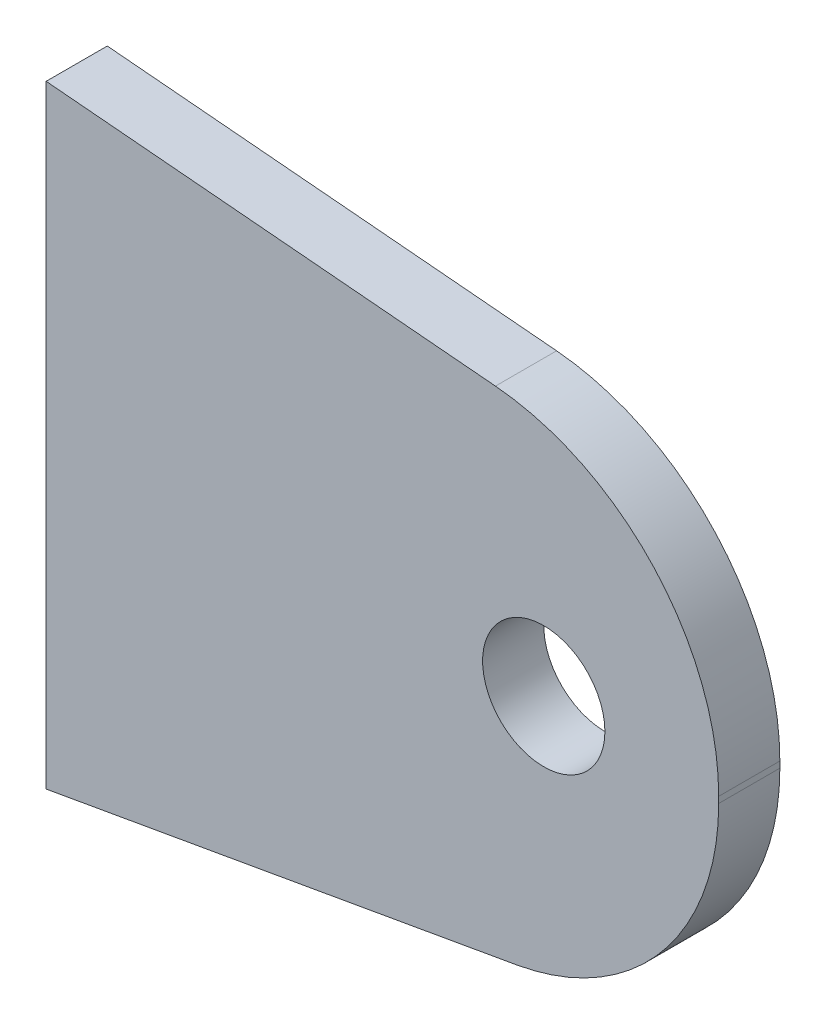
SolidWorks part; units mm, degrees
material "AISI 4340 Steel, annealed"
ref_plane "X-Y Datum" through (0, 0, 0) normal (0, 0, 1) x (1, 0, 0)
ref_plane "X-Z Datum" through (0, 0, 0) normal (0, 1, 0) x (1, 0, 0)
ref_plane "Y-Z Datum" through (0, 0, 0) normal (1, 0, 0) x (0, 0, -1)
sketch "Sketch1" plane through (0, 0, 0) normal (0, 0, 1) x (1, 0, 0)
  line L1 (-29.2806, 20.7611) -> (36.8075, 20.7611)
  line L2 (-29.2806, 20.7611) -> (-29.2806, -16.9563)
  line L3 (-29.2806, -16.9563) -> (36.8075, -16.9563)
  line L4 (36.8075, 20.7611) -> (36.8075, -16.9563)
extrude "Boss-Extrude1" add sketch "Sketch1" along normal blind 3.175
hole_wizard "1/4 (0.25) Diameter Hole1" positions "Sketch2" profile "Sketch3" hole size "1/4" standard "ANSI Inch"
sketch "Sketch2" plane through (0, 0, 3.175) normal (0, 0, 1) x (1, 0, 0)
  point P0 (-3.4399, 6.0288)
  dimension "D1" = 25.8407
  dimension "D2" = 14.7323
sketch "Sketch3" plane through (-3.4399, 6.0288, 3.175) normal (1, 0, 0) x (0, -1, 0)
  line L0 (0, 0) -> (0, 11.176)
  line L1 (0, 11.176) -> (3.175, 9.2683)
  line L2 (3.175, 9.2683) -> (3.175, 0)
  line L5 (3.175, 0) -> (0, 0)
  line L10 (0, 11.176) -> (-3.175, 9.2683) construction
  line L11 (0, -6.35) -> (0, 107.95) construction
  dimension "Hole Dia." = 6.35
  dimension "Hole Depth" = 11.176
  dimension "Drill Angle" = 118
sketch "Sketch4" plane through (0, 0, 0) normal (0, 0, -1) x (-1, 0, 0)
  line L0 (29.2806, 20.7611) -> (29.2806, -11.0682)
  line L4 (-5.6444, 17.7055) -> (-5.6444, -4.9099)
  line L5 (-5.6444, 17.7055) -> (29.2806, 20.7611)
  line L6 (29.2806, -11.0682) -> (-5.6444, -4.9099)
  line L7 (29.2806, 20.7611) -> (29.2806, -16.9563) construction
  dimension "D3" = 80
  dimension "D1" = 31.8292
  dimension "D2" = 34.925
  dimension "D5" = 85
extrude "Cut-Extrude1" cut sketch "Sketch4" against normal through all
fillet "Fillet1" radius 12.7 2 edges at (5.6444, -4.9099, 1.5875) (5.6444, 17.7055, 1.5875)
